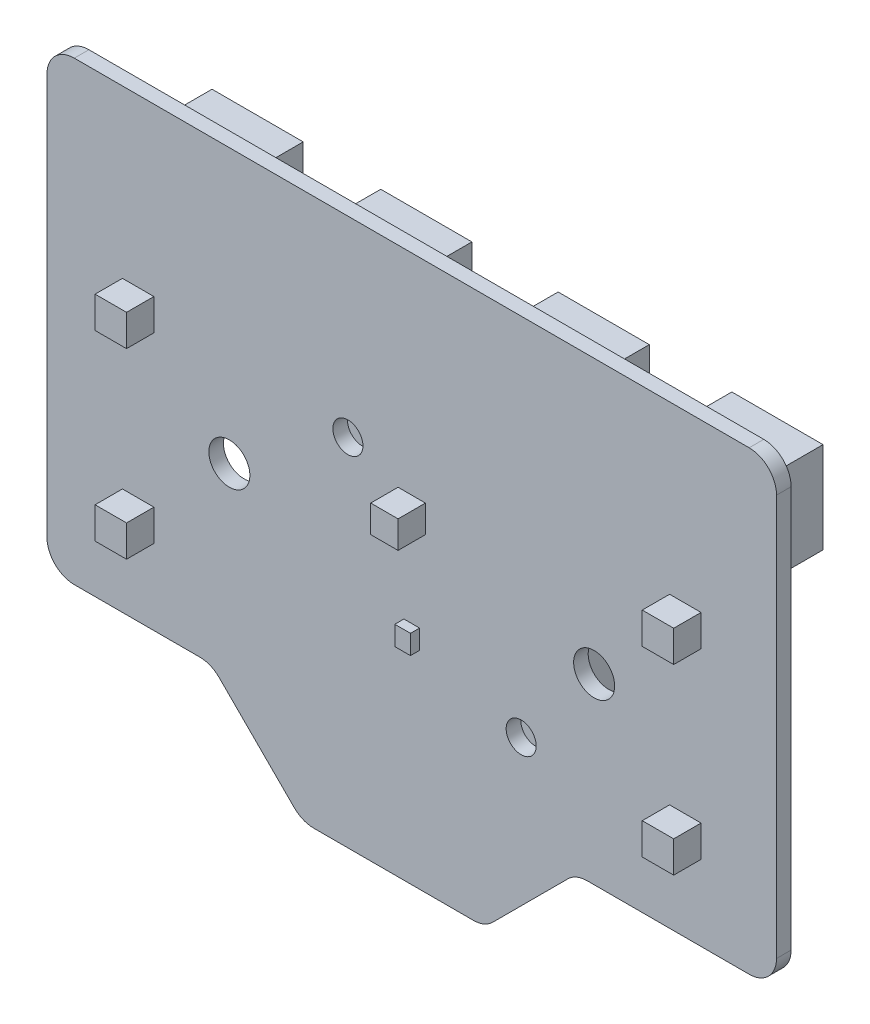
SolidWorks part; units mm, degrees
ref_plane "Plan de face" through (0, 0, 0) normal (0, 0, 1) x (1, 0, 0)
ref_plane "Plan de dessus" through (0, 0, 0) normal (0, 1, 0) x (1, 0, 0)
ref_plane "Plan de droite" through (0, 0, 0) normal (1, 0, 0) x (0, 0, -1)
sketch "Model" plane through (0, 0, 0) normal (0, 0, 1) x (1, 0, 0)
  line L0 (29.2426, -10) -> (46.7574, -10)
  line L1 (48.8787, -9.1213) -> (57.1213, -0.8787)
  line L2 (59.2426, 0) -> (77, 0)
  line L3 (27.1213, -9.1213) -> (18.8787, -0.8787)
  line L4 (16.7574, 0) -> (3, 0)
  line L5 (80, 3) -> (80, 47)
  line L6 (77, 50) -> (3, 50)
  line L7 (0, 3) -> (0, 47)
  line L8 (55, 7) -> (55, 32)
  line L9 (55, 32) -> (30, 32)
  line L10 (30, 32) -> (30, 7)
  line L11 (30, 7) -> (55, 7)
  line L12 (11.725, 31.725) -> (11.725, 28.275)
  line L13 (11.725, 28.275) -> (8.275, 28.275)
  line L14 (8.275, 28.275) -> (8.275, 31.725)
  line L15 (8.275, 31.725) -> (11.725, 31.725)
  line L16 (11.725, 11.725) -> (11.725, 8.275)
  line L17 (11.725, 8.275) -> (8.275, 8.275)
  line L18 (8.275, 8.275) -> (8.275, 11.725)
  line L19 (8.275, 11.725) -> (11.725, 11.725)
  line L20 (47.4, 42.75) -> (47.4, 45.95)
  line L21 (47.4, 45.95) -> (47.4, 47.25)
  line L22 (47.4, 47.25) -> (43.6, 47.25)
  line L23 (43.6, 47.25) -> (43.6, 45.95)
  line L24 (43.6, 45.95) -> (43.6, 42.75)
  line L25 (43.6, 42.75) -> (47.4, 42.75)
  line L26 (47.4, 45.95) -> (43.6, 45.95)
  line L27 (9.65, 43) -> (9.65, 46.2)
  line L28 (9.65, 46.2) -> (9.65, 47.5)
  line L29 (9.65, 47.5) -> (5.85, 47.5)
  line L30 (5.85, 47.5) -> (5.85, 46.2)
  line L31 (5.85, 46.2) -> (5.85, 43)
  line L32 (5.85, 43) -> (9.65, 43)
  line L33 (9.65, 46.2) -> (5.85, 46.2)
  line L34 (66.4, 42.75) -> (66.4, 45.95)
  line L35 (66.4, 45.95) -> (66.4, 47.25)
  line L36 (66.4, 47.25) -> (62.6, 47.25)
  line L37 (62.6, 47.25) -> (62.6, 45.95)
  line L38 (62.6, 45.95) -> (62.6, 42.75)
  line L39 (62.6, 42.75) -> (66.4, 42.75)
  line L40 (66.4, 45.95) -> (62.6, 45.95)
  line L41 (28.07, 42.75) -> (28.07, 45.95)
  line L42 (28.07, 45.95) -> (28.07, 47.25)
  line L43 (28.07, 47.25) -> (24.27, 47.25)
  line L44 (24.27, 47.25) -> (24.27, 45.95)
  line L45 (24.27, 45.95) -> (24.27, 42.75)
  line L46 (24.27, 42.75) -> (28.07, 42.75)
  line L47 (28.07, 45.95) -> (24.27, 45.95)
  line L48 (26.675, -5.9) -> (31, -5.9)
  line L49 (31, -5.9) -> (32, -5.9)
  line L50 (32, -5.9) -> (36.325, -5.9)
  line L51 (36.325, -5.9) -> (36.325, -1.53)
  line L52 (36.325, -1.53) -> (33.25, -1.53)
  line L53 (33.25, -1.53) -> (32.25, -1.53)
  line L54 (32.25, -1.53) -> (30.75, -1.53)
  line L55 (30.75, -1.53) -> (29.75, -1.53)
  line L56 (29.75, -1.53) -> (26.675, -1.53)
  line L57 (26.675, -1.53) -> (26.675, -5.9)
  line L58 (31, -5.9) -> (31, -6.5)
  line L59 (31, -6.5) -> (32, -6.5)
  line L60 (32, -6.5) -> (32, -5.9)
  line L61 (30.75, -1.53) -> (30.75, -0.93)
  line L62 (30.75, -0.93) -> (29.75, -0.93)
  line L63 (29.75, -0.93) -> (29.75, -1.53)
  line L64 (32.25, -1.53) -> (32.25, -0.93)
  line L65 (32.25, -0.93) -> (33.25, -0.93)
  line L66 (33.25, -0.93) -> (33.25, -1.53)
  line L67 (31.75, -5.25) -> (34.25, -5.25)
  line L68 (34.25, -5.25) -> (34.25, -3.25)
  line L69 (34.25, -3.25) -> (33.75, -2.75)
  line L70 (33.75, -2.75) -> (31.75, -2.75)
  line L71 (31.75, -2.75) -> (31.75, -5.25)
  line L72 (28.75, -5.25) -> (31.25, -5.25)
  line L73 (31.25, -5.25) -> (31.25, -2.75)
  line L74 (31.25, -2.75) -> (29.25, -2.75)
  line L75 (29.25, -2.75) -> (28.75, -3.25)
  line L76 (28.75, -3.25) -> (28.75, -5.25)
  line L77 (39.925, -5.9) -> (44.25, -5.9)
  line L78 (44.25, -5.9) -> (45.25, -5.9)
  line L79 (45.25, -5.9) -> (49.575, -5.9)
  line L80 (49.575, -5.9) -> (49.575, -1.53)
  line L81 (49.575, -1.53) -> (46.5, -1.53)
  line L82 (46.5, -1.53) -> (45.5, -1.53)
  line L83 (45.5, -1.53) -> (44, -1.53)
  line L84 (44, -1.53) -> (43, -1.53)
  line L85 (43, -1.53) -> (39.925, -1.53)
  line L86 (39.925, -1.53) -> (39.925, -5.9)
  line L87 (44.25, -5.9) -> (44.25, -6.5)
  line L88 (44.25, -6.5) -> (45.25, -6.5)
  line L89 (45.25, -6.5) -> (45.25, -5.9)
  line L90 (44, -1.53) -> (44, -0.93)
  line L91 (44, -0.93) -> (43, -0.93)
  line L92 (43, -0.93) -> (43, -1.53)
  line L93 (45.5, -1.53) -> (45.5, -0.93)
  line L94 (45.5, -0.93) -> (46.5, -0.93)
  line L95 (46.5, -0.93) -> (46.5, -1.53)
  line L96 (45, -5.25) -> (47.5, -5.25)
  line L97 (47.5, -5.25) -> (47.5, -3.25)
  line L98 (47.5, -3.25) -> (47, -2.75)
  line L99 (47, -2.75) -> (45, -2.75)
  line L100 (45, -2.75) -> (45, -5.25)
  line L101 (42, -5.25) -> (44.5, -5.25)
  line L102 (44.5, -5.25) -> (44.5, -2.75)
  line L103 (44.5, -2.75) -> (42.5, -2.75)
  line L104 (42.5, -2.75) -> (42, -3.25)
  line L105 (42, -3.25) -> (42, -5.25)
  line L106 (21.5, 38) -> (21.5, 48)
  line L107 (21.5, 48) -> (11.5, 48)
  line L108 (11.5, 48) -> (11.5, 38)
  line L109 (11.5, 38) -> (21.5, 38)
  line L110 (16.2908, 37.35) -> (16.2908, 36.4508)
  line L111 (16.2908, 36.4508) -> (15.6913, 36.4508)
  line L112 (15.37, 37.0502) -> (15.0703, 37.35)
  line L113 (15.0703, 37.35) -> (15.0703, 36.4508)
  line L114 (15.37, 36.4508) -> (14.7705, 36.4508)
  line L115 (78.5, 37.75) -> (78.5, 47.75)
  line L116 (78.5, 47.75) -> (68.5, 47.75)
  line L117 (68.5, 47.75) -> (68.5, 37.75)
  line L118 (68.5, 37.75) -> (78.5, 37.75)
  line L119 (73.2908, 37.1) -> (73.2908, 36.2008)
  line L120 (73.2908, 36.2008) -> (72.6913, 36.2008)
  line L121 (71.7705, 36.2008) -> (72.37, 36.2008)
  line L122 (72.37, 36.2008) -> (71.7705, 36.8002)
  line L123 (71.7705, 36.8002) -> (71.7705, 36.9501)
  line L124 (71.7705, 36.9501) -> (71.9204, 37.1)
  line L125 (71.9204, 37.1) -> (72.2201, 37.1)
  line L126 (72.2201, 37.1) -> (72.37, 36.9501)
  line L127 (40, 37.75) -> (40, 47.75)
  line L128 (40, 47.75) -> (30, 47.75)
  line L129 (30, 47.75) -> (30, 37.75)
  line L130 (30, 37.75) -> (40, 37.75)
  line L131 (34.7908, 37.1) -> (34.7908, 36.2008)
  line L132 (34.7908, 36.2008) -> (34.1913, 36.2008)
  line L133 (33.87, 36.9501) -> (33.7201, 37.1)
  line L134 (33.7201, 37.1) -> (33.4204, 37.1)
  line L135 (33.4204, 37.1) -> (33.2705, 36.9501)
  line L136 (33.2705, 36.9501) -> (33.2705, 36.8002)
  line L137 (33.2705, 36.8002) -> (33.4204, 36.6504)
  line L138 (33.4204, 36.6504) -> (33.5703, 36.6504)
  line L139 (33.4204, 36.6504) -> (33.2705, 36.5005)
  line L140 (33.2705, 36.5005) -> (33.2705, 36.3507)
  line L141 (33.2705, 36.3507) -> (33.4204, 36.2008)
  line L142 (33.4204, 36.2008) -> (33.7201, 36.2008)
  line L143 (33.7201, 36.2008) -> (33.87, 36.3507)
  line L144 (59.45, 37.72) -> (59.45, 47.72)
  line L145 (59.45, 47.72) -> (49.45, 47.72)
  line L146 (49.45, 47.72) -> (49.45, 37.72)
  line L147 (49.45, 37.72) -> (59.45, 37.72)
  line L148 (54.2408, 37.07) -> (54.2408, 36.1708)
  line L149 (54.2408, 36.1708) -> (53.6413, 36.1708)
  line L150 (52.7205, 37.07) -> (53.32, 37.07)
  line L151 (53.32, 37.07) -> (53.32, 36.6204)
  line L152 (53.32, 36.6204) -> (53.0203, 36.7702)
  line L153 (53.0203, 36.7702) -> (52.8704, 36.7702)
  line L154 (52.8704, 36.7702) -> (52.7205, 36.6204)
  line L155 (52.7205, 36.6204) -> (52.7205, 36.3207)
  line L156 (52.7205, 36.3207) -> (52.8704, 36.1708)
  line L157 (52.8704, 36.1708) -> (53.1701, 36.1708)
  line L158 (53.1701, 36.1708) -> (53.32, 36.3207)
  line L159 (68.275, 31.725) -> (71.725, 31.725)
  line L160 (71.725, 31.725) -> (71.725, 28.275)
  line L161 (71.725, 28.275) -> (68.275, 28.275)
  line L162 (68.275, 28.275) -> (68.275, 31.725)
  line L163 (68.275, 11.725) -> (71.725, 11.725)
  line L164 (71.725, 11.725) -> (71.725, 8.275)
  line L165 (71.725, 8.275) -> (68.275, 8.275)
  line L166 (68.275, 8.275) -> (68.275, 11.725)
  line L167 (10.422, 37.44) -> (10.422, 39.06)
  line L168 (7.578, 39.06) -> (7.578, 37.44)
  line L169 (8.478, 37.44) -> (9.522, 37.44)
  line L170 (8.572, 39.06) -> (8.478, 39.06)
  line L171 (9.522, 39.06) -> (9.428, 39.06)
  line L172 (7.672, 39.06) -> (7.578, 39.06)
  line L173 (10.422, 39.06) -> (10.328, 39.06)
  line L174 (10.328, 37.44) -> (10.422, 37.44)
  line L175 (7.578, 37.44) -> (7.672, 37.44)
  line L176 (66.922, 36.69) -> (66.922, 38.31)
  line L177 (64.078, 38.31) -> (64.078, 36.69)
  line L178 (64.978, 36.69) -> (66.022, 36.69)
  line L179 (65.072, 38.31) -> (64.978, 38.31)
  line L180 (66.022, 38.31) -> (65.928, 38.31)
  line L181 (64.172, 38.31) -> (64.078, 38.31)
  line L182 (66.922, 38.31) -> (66.828, 38.31)
  line L183 (66.828, 36.69) -> (66.922, 36.69)
  line L184 (64.078, 36.69) -> (64.172, 36.69)
  line L185 (28.922, 36.94) -> (28.922, 38.56)
  line L186 (26.078, 38.56) -> (26.078, 36.94)
  line L187 (26.978, 36.94) -> (28.022, 36.94)
  line L188 (27.072, 38.56) -> (26.978, 38.56)
  line L189 (28.022, 38.56) -> (27.928, 38.56)
  line L190 (26.172, 38.56) -> (26.078, 38.56)
  line L191 (28.922, 38.56) -> (28.828, 38.56)
  line L192 (28.828, 36.94) -> (28.922, 36.94)
  line L193 (26.078, 36.94) -> (26.172, 36.94)
  line L194 (47.922, 37.19) -> (47.922, 38.81)
  line L195 (45.078, 38.81) -> (45.078, 37.19)
  line L196 (45.978, 37.19) -> (47.022, 37.19)
  line L197 (46.072, 38.81) -> (45.978, 38.81)
  line L198 (47.022, 38.81) -> (46.928, 38.81)
  line L199 (45.172, 38.81) -> (45.078, 38.81)
  line L200 (47.922, 38.81) -> (47.828, 38.81)
  line L201 (47.828, 37.19) -> (47.922, 37.19)
  line L202 (45.078, 37.19) -> (45.172, 37.19)
  line L203 (40.86, 14.81) -> (40.86, 13.86)
  line L204 (40.86, 13.86) -> (40.75, 13.75)
  line L205 (40.75, 13.75) -> (40.86, 13.64)
  line L206 (40.86, 13.64) -> (40.86, 12.69)
  line L207 (40.86, 12.69) -> (39.14, 12.69)
  line L208 (39.14, 12.69) -> (39.14, 14.81)
  line L209 (39.14, 14.81) -> (40.86, 14.81)
  line L210 (41.5, 24) -> (38.5, 24)
  line L211 (38.5, 24) -> (38.5, 27)
  line L212 (38.5, 27) -> (41.5, 27)
  line L213 (41.5, 27) -> (41.5, 24)
  arc A0 (46.7574, -10) -> (48.8787, -9.1213) centre (46.7574, -7) ccw
  arc A1 (59.2426, 0) -> (57.1213, -0.8787) centre (59.2426, -3) ccw
  arc A2 (27.1213, -9.1213) -> (29.2426, -10) centre (29.2426, -7) ccw
  arc A3 (18.8787, -0.8787) -> (16.7574, 0) centre (16.7574, -3) ccw
  arc A4 (77, 0) -> (80, 3) centre (77, 3) ccw
  arc A5 (80, 47) -> (77, 50) centre (77, 47) ccw
  arc A6 (3, 50) -> (0, 47) centre (3, 47) ccw
  arc A7 (0, 3) -> (3, 0) centre (3, 3) ccw
  circle A8 centre (20, 20) radius 2.25
  circle A9 centre (60, 20) radius 2.25
  circle A10 centre (33, 29) radius 1.65
  circle A11 centre (52, 10) radius 1.65
  circle A12 centre (27, -5.96) radius 0.55
  circle A13 centre (36, -5.96) radius 0.55
  circle A14 centre (40.25, -5.96) radius 0.55
  circle A15 centre (49.25, -5.96) radius 0.55
  arc A16 (55.05, 32) -> (54.95, 32) centre (55, 32) ccw
  arc A17 (54.95, 7) -> (55.05, 7) centre (55, 7) ccw
  arc A18 (30, 32.05) -> (30, 31.95) centre (30, 32) ccw
  arc A19 (55, 31.95) -> (55, 32.05) centre (55, 32) ccw
  arc A20 (29.95, 7) -> (30.05, 7) centre (30, 7) ccw
  arc A21 (30.05, 32) -> (29.95, 32) centre (30, 32) ccw
  arc A22 (55, 6.95) -> (55, 7.05) centre (55, 7) ccw
  arc A23 (30, 7.05) -> (30, 6.95) centre (30, 7) ccw
  arc A24 (11.7125, 28.275) -> (11.7375, 28.275) centre (11.725, 28.275) ccw
  arc A25 (11.7375, 31.725) -> (11.7125, 31.725) centre (11.725, 31.725) ccw
  arc A26 (8.275, 28.2875) -> (8.275, 28.2625) centre (8.275, 28.275) ccw
  arc A27 (11.725, 28.2625) -> (11.725, 28.2875) centre (11.725, 28.275) ccw
  arc A28 (8.2875, 31.725) -> (8.2625, 31.725) centre (8.275, 31.725) ccw
  arc A29 (8.2625, 28.275) -> (8.2875, 28.275) centre (8.275, 28.275) ccw
  arc A30 (11.725, 31.7125) -> (11.725, 31.7375) centre (11.725, 31.725) ccw
  arc A31 (8.275, 31.7375) -> (8.275, 31.7125) centre (8.275, 31.725) ccw
  arc A32 (11.7125, 8.275) -> (11.7375, 8.275) centre (11.725, 8.275) ccw
  arc A33 (11.7375, 11.725) -> (11.7125, 11.725) centre (11.725, 11.725) ccw
  arc A34 (8.275, 8.2875) -> (8.275, 8.2625) centre (8.275, 8.275) ccw
  arc A35 (11.725, 8.2625) -> (11.725, 8.2875) centre (11.725, 8.275) ccw
  arc A36 (8.2875, 11.725) -> (8.2625, 11.725) centre (8.275, 11.725) ccw
  arc A37 (8.2625, 8.275) -> (8.2875, 8.275) centre (8.275, 8.275) ccw
  arc A38 (11.725, 11.7125) -> (11.725, 11.7375) centre (11.725, 11.725) ccw
  arc A39 (8.275, 11.7375) -> (8.275, 11.7125) centre (8.275, 11.725) ccw
  arc A40 (47.4635, 45.95) -> (47.3365, 45.95) centre (47.4, 45.95) ccw
  arc A41 (47.3365, 42.75) -> (47.4635, 42.75) centre (47.4, 42.75) ccw
  arc A42 (47.4635, 47.25) -> (47.3365, 47.25) centre (47.4, 47.25) ccw
  arc A43 (47.3365, 45.95) -> (47.4635, 45.95) centre (47.4, 45.95) ccw
  arc A44 (43.6, 47.3135) -> (43.6, 47.1865) centre (43.6, 47.25) ccw
  arc A45 (47.4, 47.1865) -> (47.4, 47.3135) centre (47.4, 47.25) ccw
  arc A46 (43.5365, 45.95) -> (43.6635, 45.95) centre (43.6, 45.95) ccw
  arc A47 (43.6635, 47.25) -> (43.5365, 47.25) centre (43.6, 47.25) ccw
  arc A48 (43.5365, 42.75) -> (43.6635, 42.75) centre (43.6, 42.75) ccw
  arc A49 (43.6635, 45.95) -> (43.5365, 45.95) centre (43.6, 45.95) ccw
  arc A50 (47.4, 42.6865) -> (47.4, 42.8135) centre (47.4, 42.75) ccw
  arc A51 (43.6, 42.8135) -> (43.6, 42.6865) centre (43.6, 42.75) ccw
  arc A52 (43.6, 46.0135) -> (43.6, 45.8865) centre (43.6, 45.95) ccw
  arc A53 (47.4, 45.8865) -> (47.4, 46.0135) centre (47.4, 45.95) ccw
  arc A54 (9.7135, 46.2) -> (9.5865, 46.2) centre (9.65, 46.2) ccw
  arc A55 (9.5865, 43) -> (9.7135, 43) centre (9.65, 43) ccw
  arc A56 (9.7135, 47.5) -> (9.5865, 47.5) centre (9.65, 47.5) ccw
  arc A57 (9.5865, 46.2) -> (9.7135, 46.2) centre (9.65, 46.2) ccw
  arc A58 (5.85, 47.5635) -> (5.85, 47.4365) centre (5.85, 47.5) ccw
  arc A59 (9.65, 47.4365) -> (9.65, 47.5635) centre (9.65, 47.5) ccw
  arc A60 (5.7865, 46.2) -> (5.9135, 46.2) centre (5.85, 46.2) ccw
  arc A61 (5.9135, 47.5) -> (5.7865, 47.5) centre (5.85, 47.5) ccw
  arc A62 (5.7865, 43) -> (5.9135, 43) centre (5.85, 43) ccw
  arc A63 (5.9135, 46.2) -> (5.7865, 46.2) centre (5.85, 46.2) ccw
  arc A64 (9.65, 42.9365) -> (9.65, 43.0635) centre (9.65, 43) ccw
  arc A65 (5.85, 43.0635) -> (5.85, 42.9365) centre (5.85, 43) ccw
  arc A66 (5.85, 46.2635) -> (5.85, 46.1365) centre (5.85, 46.2) ccw
  arc A67 (9.65, 46.1365) -> (9.65, 46.2635) centre (9.65, 46.2) ccw
  arc A68 (66.4635, 45.95) -> (66.3365, 45.95) centre (66.4, 45.95) ccw
  arc A69 (66.3365, 42.75) -> (66.4635, 42.75) centre (66.4, 42.75) ccw
  arc A70 (66.4635, 47.25) -> (66.3365, 47.25) centre (66.4, 47.25) ccw
  arc A71 (66.3365, 45.95) -> (66.4635, 45.95) centre (66.4, 45.95) ccw
  arc A72 (62.6, 47.3135) -> (62.6, 47.1865) centre (62.6, 47.25) ccw
  arc A73 (66.4, 47.1865) -> (66.4, 47.3135) centre (66.4, 47.25) ccw
  arc A74 (62.5365, 45.95) -> (62.6635, 45.95) centre (62.6, 45.95) ccw
  arc A75 (62.6635, 47.25) -> (62.5365, 47.25) centre (62.6, 47.25) ccw
  arc A76 (62.5365, 42.75) -> (62.6635, 42.75) centre (62.6, 42.75) ccw
  arc A77 (62.6635, 45.95) -> (62.5365, 45.95) centre (62.6, 45.95) ccw
  arc A78 (66.4, 42.6865) -> (66.4, 42.8135) centre (66.4, 42.75) ccw
  arc A79 (62.6, 42.8135) -> (62.6, 42.6865) centre (62.6, 42.75) ccw
  arc A80 (62.6, 46.0135) -> (62.6, 45.8865) centre (62.6, 45.95) ccw
  arc A81 (66.4, 45.8865) -> (66.4, 46.0135) centre (66.4, 45.95) ccw
  arc A82 (28.1335, 45.95) -> (28.0065, 45.95) centre (28.07, 45.95) ccw
  arc A83 (28.0065, 42.75) -> (28.1335, 42.75) centre (28.07, 42.75) ccw
  arc A84 (28.1335, 47.25) -> (28.0065, 47.25) centre (28.07, 47.25) ccw
  arc A85 (28.0065, 45.95) -> (28.1335, 45.95) centre (28.07, 45.95) ccw
  arc A86 (24.27, 47.3135) -> (24.27, 47.1865) centre (24.27, 47.25) ccw
  arc A87 (28.07, 47.1865) -> (28.07, 47.3135) centre (28.07, 47.25) ccw
  arc A88 (24.2065, 45.95) -> (24.3335, 45.95) centre (24.27, 45.95) ccw
  arc A89 (24.3335, 47.25) -> (24.2065, 47.25) centre (24.27, 47.25) ccw
  arc A90 (24.2065, 42.75) -> (24.3335, 42.75) centre (24.27, 42.75) ccw
  arc A91 (24.3335, 45.95) -> (24.2065, 45.95) centre (24.27, 45.95) ccw
  arc A92 (28.07, 42.6865) -> (28.07, 42.8135) centre (28.07, 42.75) ccw
  arc A93 (24.27, 42.8135) -> (24.27, 42.6865) centre (24.27, 42.75) ccw
  arc A94 (24.27, 46.0135) -> (24.27, 45.8865) centre (24.27, 45.95) ccw
  arc A95 (28.07, 45.8865) -> (28.07, 46.0135) centre (28.07, 45.95) ccw
  arc A96 (31, -5.9318) -> (31, -5.8683) centre (31, -5.9001) ccw
  arc A97 (26.675, -5.8683) -> (26.675, -5.9318) centre (26.675, -5.9001) ccw
  arc A98 (32, -5.9318) -> (32, -5.8683) centre (32, -5.9001) ccw
  arc A99 (31, -5.8683) -> (31, -5.9318) centre (31, -5.9001) ccw
  arc A100 (36.325, -5.9318) -> (36.325, -5.8683) centre (36.325, -5.9001) ccw
  arc A101 (32, -5.8683) -> (32, -5.9318) centre (32, -5.9001) ccw
  arc A102 (36.3568, -1.53) -> (36.2933, -1.53) centre (36.325, -1.53) ccw
  arc A103 (36.2933, -5.9) -> (36.3568, -5.9) centre (36.325, -5.9) ccw
  arc A104 (33.25, -1.4983) -> (33.25, -1.5617) centre (33.25, -1.53) ccw
  arc A105 (36.325, -1.5617) -> (36.325, -1.4983) centre (36.325, -1.53) ccw
  arc A106 (32.25, -1.4983) -> (32.25, -1.5617) centre (32.25, -1.53) ccw
  arc A107 (33.25, -1.5617) -> (33.25, -1.4983) centre (33.25, -1.53) ccw
  arc A108 (30.75, -1.4983) -> (30.75, -1.5617) centre (30.75, -1.53) ccw
  arc A109 (32.25, -1.5617) -> (32.25, -1.4983) centre (32.25, -1.53) ccw
  arc A110 (29.75, -1.4983) -> (29.75, -1.5617) centre (29.75, -1.53) ccw
  arc A111 (30.75, -1.5617) -> (30.75, -1.4983) centre (30.75, -1.53) ccw
  arc A112 (26.675, -1.4983) -> (26.675, -1.5617) centre (26.675, -1.53) ccw
  arc A113 (29.75, -1.5617) -> (29.75, -1.4983) centre (29.75, -1.53) ccw
  arc A114 (26.6433, -5.9) -> (26.7067, -5.9) centre (26.675, -5.9) ccw
  arc A115 (26.7067, -1.53) -> (26.6433, -1.53) centre (26.675, -1.53) ccw
  arc A116 (30.9683, -6.5) -> (31.0317, -6.5) centre (31, -6.5) ccw
  arc A117 (31.0317, -5.9) -> (30.9683, -5.9) centre (31, -5.9) ccw
  arc A118 (32, -6.5317) -> (32, -6.4683) centre (32, -6.5) ccw
  arc A119 (31, -6.4683) -> (31, -6.5317) centre (31, -6.5) ccw
  arc A120 (32.0318, -5.9) -> (31.9683, -5.9) centre (32.0001, -5.9) ccw
  arc A121 (31.9683, -6.5) -> (32.0318, -6.5) centre (32.0001, -6.5) ccw
  arc A122 (30.7817, -0.93) -> (30.7183, -0.93) centre (30.75, -0.93) ccw
  arc A123 (30.7183, -1.53) -> (30.7817, -1.53) centre (30.75, -1.53) ccw
  arc A124 (29.75, -0.8982) -> (29.75, -0.9618) centre (29.75, -0.93) ccw
  arc A125 (30.75, -0.9618) -> (30.75, -0.8982) centre (30.75, -0.93) ccw
  arc A126 (29.7183, -1.53) -> (29.7817, -1.53) centre (29.75, -1.53) ccw
  arc A127 (29.7817, -0.93) -> (29.7183, -0.93) centre (29.75, -0.93) ccw
  arc A128 (32.2818, -0.93) -> (32.2182, -0.93) centre (32.25, -0.93) ccw
  arc A129 (32.2182, -1.53) -> (32.2818, -1.53) centre (32.25, -1.53) ccw
  arc A130 (33.25, -0.9618) -> (33.25, -0.8982) centre (33.25, -0.93) ccw
  arc A131 (32.25, -0.8982) -> (32.25, -0.9618) centre (32.25, -0.93) ccw
  arc A132 (33.2182, -1.53) -> (33.2818, -1.53) centre (33.25, -1.53) ccw
  arc A133 (33.2818, -0.93) -> (33.2182, -0.93) centre (33.25, -0.93) ccw
  arc A134 (34.25, -5.2817) -> (34.25, -5.2183) centre (34.25, -5.25) ccw
  arc A135 (31.75, -5.2183) -> (31.75, -5.2817) centre (31.75, -5.25) ccw
  arc A136 (34.2818, -3.25) -> (34.2182, -3.25) centre (34.25, -3.25) ccw
  arc A137 (34.2182, -5.25) -> (34.2818, -5.25) centre (34.25, -5.25) ccw
  arc A138 (33.7725, -2.7275) -> (33.7275, -2.7725) centre (33.75, -2.75) ccw
  arc A139 (34.2275, -3.2725) -> (34.2725, -3.2275) centre (34.25, -3.25) ccw
  arc A140 (31.75, -2.7182) -> (31.75, -2.7818) centre (31.75, -2.75) ccw
  arc A141 (33.75, -2.7818) -> (33.75, -2.7182) centre (33.75, -2.75) ccw
  arc A142 (31.7183, -5.25) -> (31.7817, -5.25) centre (31.75, -5.25) ccw
  arc A143 (31.7817, -2.75) -> (31.7183, -2.75) centre (31.75, -2.75) ccw
  arc A144 (31.25, -5.2817) -> (31.25, -5.2183) centre (31.25, -5.25) ccw
  arc A145 (28.75, -5.2183) -> (28.75, -5.2817) centre (28.75, -5.25) ccw
  arc A146 (31.2817, -2.75) -> (31.2183, -2.75) centre (31.25, -2.75) ccw
  arc A147 (31.2183, -5.25) -> (31.2817, -5.25) centre (31.25, -5.25) ccw
  arc A148 (29.25, -2.7182) -> (29.25, -2.7818) centre (29.25, -2.75) ccw
  arc A149 (31.25, -2.7818) -> (31.25, -2.7182) centre (31.25, -2.75) ccw
  arc A150 (28.7275, -3.2275) -> (28.7725, -3.2725) centre (28.75, -3.25) ccw
  arc A151 (29.2725, -2.7725) -> (29.2275, -2.7275) centre (29.25, -2.75) ccw
  arc A152 (28.7183, -5.25) -> (28.7817, -5.25) centre (28.75, -5.25) ccw
  arc A153 (28.7817, -3.25) -> (28.7183, -3.25) centre (28.75, -3.25) ccw
  arc A154 (44.25, -5.9318) -> (44.25, -5.8683) centre (44.25, -5.9001) ccw
  arc A155 (39.925, -5.8683) -> (39.925, -5.9318) centre (39.925, -5.9001) ccw
  arc A156 (45.25, -5.9318) -> (45.25, -5.8683) centre (45.25, -5.9001) ccw
  arc A157 (44.25, -5.8683) -> (44.25, -5.9318) centre (44.25, -5.9001) ccw
  arc A158 (49.575, -5.9318) -> (49.575, -5.8683) centre (49.575, -5.9001) ccw
  arc A159 (45.25, -5.8683) -> (45.25, -5.9318) centre (45.25, -5.9001) ccw
  arc A160 (49.6068, -1.53) -> (49.5433, -1.53) centre (49.5751, -1.53) ccw
  arc A161 (49.5433, -5.9) -> (49.6068, -5.9) centre (49.5751, -5.9) ccw
  arc A162 (46.5, -1.4983) -> (46.5, -1.5617) centre (46.5, -1.53) ccw
  arc A163 (49.575, -1.5617) -> (49.575, -1.4983) centre (49.575, -1.53) ccw
  arc A164 (45.5, -1.4983) -> (45.5, -1.5617) centre (45.5, -1.53) ccw
  arc A165 (46.5, -1.5617) -> (46.5, -1.4983) centre (46.5, -1.53) ccw
  arc A166 (44, -1.4983) -> (44, -1.5617) centre (44, -1.53) ccw
  arc A167 (45.5, -1.5617) -> (45.5, -1.4983) centre (45.5, -1.53) ccw
  arc A168 (43, -1.4983) -> (43, -1.5617) centre (43, -1.53) ccw
  arc A169 (44, -1.5617) -> (44, -1.4983) centre (44, -1.53) ccw
  arc A170 (39.925, -1.4983) -> (39.925, -1.5617) centre (39.925, -1.53) ccw
  arc A171 (43, -1.5617) -> (43, -1.4983) centre (43, -1.53) ccw
  arc A172 (39.8933, -5.9) -> (39.9568, -5.9) centre (39.9251, -5.9) ccw
  arc A173 (39.9568, -1.53) -> (39.8933, -1.53) centre (39.9251, -1.53) ccw
  arc A174 (44.2182, -6.5) -> (44.2818, -6.5) centre (44.25, -6.5) ccw
  arc A175 (44.2818, -5.9) -> (44.2182, -5.9) centre (44.25, -5.9) ccw
  arc A176 (45.25, -6.5317) -> (45.25, -6.4683) centre (45.25, -6.5) ccw
  arc A177 (44.25, -6.4683) -> (44.25, -6.5317) centre (44.25, -6.5) ccw
  arc A178 (45.2818, -5.9) -> (45.2182, -5.9) centre (45.25, -5.9) ccw
  arc A179 (45.2182, -6.5) -> (45.2818, -6.5) centre (45.25, -6.5) ccw
  arc A180 (44.0318, -0.93) -> (43.9682, -0.93) centre (44, -0.93) ccw
  arc A181 (43.9682, -1.53) -> (44.0318, -1.53) centre (44, -1.53) ccw
  arc A182 (43, -0.8982) -> (43, -0.9618) centre (43, -0.93) ccw
  arc A183 (44, -0.9618) -> (44, -0.8982) centre (44, -0.93) ccw
  arc A184 (42.9682, -1.53) -> (43.0318, -1.53) centre (43, -1.53) ccw
  arc A185 (43.0318, -0.93) -> (42.9682, -0.93) centre (43, -0.93) ccw
  arc A186 (45.5318, -0.93) -> (45.4682, -0.93) centre (45.5, -0.93) ccw
  arc A187 (45.4682, -1.53) -> (45.5318, -1.53) centre (45.5, -1.53) ccw
  arc A188 (46.5, -0.9618) -> (46.5, -0.8982) centre (46.5, -0.93) ccw
  arc A189 (45.5, -0.8982) -> (45.5, -0.9618) centre (45.5, -0.93) ccw
  arc A190 (46.4682, -1.53) -> (46.5318, -1.53) centre (46.5, -1.53) ccw
  arc A191 (46.5318, -0.93) -> (46.4682, -0.93) centre (46.5, -0.93) ccw
  arc A192 (47.5, -5.2817) -> (47.5, -5.2183) centre (47.5, -5.25) ccw
  arc A193 (45, -5.2183) -> (45, -5.2817) centre (45, -5.25) ccw
  arc A194 (47.5318, -3.25) -> (47.4682, -3.25) centre (47.5, -3.25) ccw
  arc A195 (47.4682, -5.25) -> (47.5318, -5.25) centre (47.5, -5.25) ccw
  arc A196 (47.0225, -2.7275) -> (46.9775, -2.7725) centre (47, -2.75) ccw
  arc A197 (47.4775, -3.2725) -> (47.5225, -3.2275) centre (47.5, -3.25) ccw
  arc A198 (45, -2.7182) -> (45, -2.7818) centre (45, -2.75) ccw
  arc A199 (47, -2.7818) -> (47, -2.7182) centre (47, -2.75) ccw
  arc A200 (44.9682, -5.25) -> (45.0318, -5.25) centre (45, -5.25) ccw
  arc A201 (45.0318, -2.75) -> (44.9682, -2.75) centre (45, -2.75) ccw
  arc A202 (44.5, -5.2817) -> (44.5, -5.2183) centre (44.5, -5.25) ccw
  arc A203 (42, -5.2183) -> (42, -5.2817) centre (42, -5.25) ccw
  arc A204 (44.5318, -2.75) -> (44.4682, -2.75) centre (44.5, -2.75) ccw
  arc A205 (44.4682, -5.25) -> (44.5318, -5.25) centre (44.5, -5.25) ccw
  arc A206 (42.5, -2.7182) -> (42.5, -2.7818) centre (42.5, -2.75) ccw
  arc A207 (44.5, -2.7818) -> (44.5, -2.7182) centre (44.5, -2.75) ccw
  arc A208 (41.9775, -3.2275) -> (42.0225, -3.2725) centre (42, -3.25) ccw
  arc A209 (42.5225, -2.7725) -> (42.4775, -2.7275) centre (42.5, -2.75) ccw
  arc A210 (41.9682, -5.25) -> (42.0318, -5.25) centre (42, -5.25) ccw
  arc A211 (42.0318, -3.25) -> (41.9682, -3.25) centre (42, -3.25) ccw
  arc A212 (21.525, 48) -> (21.475, 48) centre (21.5, 48) ccw
  arc A213 (21.475, 38) -> (21.525, 38) centre (21.5, 38) ccw
  arc A214 (11.5, 48.025) -> (11.5, 47.975) centre (11.5, 48) ccw
  arc A215 (21.5, 47.975) -> (21.5, 48.025) centre (21.5, 48) ccw
  arc A216 (11.475, 38) -> (11.525, 38) centre (11.5, 38) ccw
  arc A217 (11.525, 48) -> (11.475, 48) centre (11.5, 48) ccw
  arc A218 (21.5, 37.975) -> (21.5, 38.025) centre (21.5, 38) ccw
  arc A219 (11.5, 38.025) -> (11.5, 37.975) centre (11.5, 38) ccw
  arc A220 (16.2654, 36.4508) -> (16.3162, 36.4508) centre (16.2908, 36.4508) ccw
  arc A221 (16.3162, 37.35) -> (16.2654, 37.35) centre (16.2908, 37.35) ccw
  arc A222 (15.6913, 36.4762) -> (15.6913, 36.4254) centre (15.6913, 36.4508) ccw
  arc A223 (16.2908, 36.4254) -> (16.2908, 36.4762) centre (16.2908, 36.4508) ccw
  arc A224 (15.0882, 37.3679) -> (15.0523, 37.332) centre (15.0702, 37.35) ccw
  arc A225 (15.352, 37.0323) -> (15.3879, 37.0682) centre (15.37, 37.0502) ccw
  arc A226 (15.0449, 36.4508) -> (15.0957, 36.4508) centre (15.0703, 36.4508) ccw
  arc A227 (15.0957, 37.35) -> (15.0449, 37.35) centre (15.0703, 37.35) ccw
  arc A228 (14.7705, 36.4762) -> (14.7705, 36.4254) centre (14.7705, 36.4508) ccw
  arc A229 (15.37, 36.4254) -> (15.37, 36.4762) centre (15.37, 36.4508) ccw
  arc A230 (78.525, 47.75) -> (78.475, 47.75) centre (78.5, 47.75) ccw
  arc A231 (78.475, 37.75) -> (78.525, 37.75) centre (78.5, 37.75) ccw
  arc A232 (68.5, 47.775) -> (68.5, 47.725) centre (68.5, 47.75) ccw
  arc A233 (78.5, 47.725) -> (78.5, 47.775) centre (78.5, 47.75) ccw
  arc A234 (68.475, 37.75) -> (68.525, 37.75) centre (68.5, 37.75) ccw
  arc A235 (68.525, 47.75) -> (68.475, 47.75) centre (68.5, 47.75) ccw
  arc A236 (78.5, 37.725) -> (78.5, 37.775) centre (78.5, 37.75) ccw
  arc A237 (68.5, 37.775) -> (68.5, 37.725) centre (68.5, 37.75) ccw
  arc A238 (73.2654, 36.2008) -> (73.3162, 36.2008) centre (73.2908, 36.2008) ccw
  arc A239 (73.3162, 37.1) -> (73.2654, 37.1) centre (73.2908, 37.1) ccw
  arc A240 (72.6913, 36.2262) -> (72.6913, 36.1754) centre (72.6913, 36.2008) ccw
  arc A241 (73.2908, 36.1754) -> (73.2908, 36.2262) centre (73.2908, 36.2008) ccw
  arc A242 (72.37, 36.1754) -> (72.37, 36.2262) centre (72.37, 36.2008) ccw
  arc A243 (71.7705, 36.2262) -> (71.7705, 36.1754) centre (71.7705, 36.2008) ccw
  arc A244 (71.7885, 36.8182) -> (71.7526, 36.7823) centre (71.7706, 36.8002) ccw
  arc A245 (72.352, 36.1828) -> (72.3879, 36.2188) centre (72.37, 36.2008) ccw
  arc A246 (71.7959, 36.9501) -> (71.7451, 36.9501) centre (71.7705, 36.9501) ccw
  arc A247 (71.7451, 36.8002) -> (71.7959, 36.8002) centre (71.7705, 36.8002) ccw
  arc A248 (71.9384, 37.082) -> (71.9024, 37.1179) centre (71.9204, 37.1) ccw
  arc A249 (71.7526, 36.9681) -> (71.7885, 36.9321) centre (71.7706, 36.9501) ccw
  arc A250 (72.2201, 37.0746) -> (72.2201, 37.1254) centre (72.2201, 37.1) ccw
  arc A251 (71.9204, 37.1254) -> (71.9204, 37.0746) centre (71.9204, 37.1) ccw
  arc A252 (72.352, 36.9321) -> (72.3879, 36.9681) centre (72.37, 36.9501) ccw
  arc A253 (72.2381, 37.1179) -> (72.2022, 37.082) centre (72.2202, 37.1) ccw
  arc A254 (40.025, 47.75) -> (39.975, 47.75) centre (40, 47.75) ccw
  arc A255 (39.975, 37.75) -> (40.025, 37.75) centre (40, 37.75) ccw
  arc A256 (30, 47.775) -> (30, 47.725) centre (30, 47.75) ccw
  arc A257 (40, 47.725) -> (40, 47.775) centre (40, 47.75) ccw
  arc A258 (29.975, 37.75) -> (30.025, 37.75) centre (30, 37.75) ccw
  arc A259 (30.025, 47.75) -> (29.975, 47.75) centre (30, 47.75) ccw
  arc A260 (40, 37.725) -> (40, 37.775) centre (40, 37.75) ccw
  arc A261 (30, 37.775) -> (30, 37.725) centre (30, 37.75) ccw
  arc A262 (34.7654, 36.2008) -> (34.8162, 36.2008) centre (34.7908, 36.2008) ccw
  arc A263 (34.8162, 37.1) -> (34.7654, 37.1) centre (34.7908, 37.1) ccw
  arc A264 (34.1913, 36.2262) -> (34.1913, 36.1754) centre (34.1913, 36.2008) ccw
  arc A265 (34.7908, 36.1754) -> (34.7908, 36.2262) centre (34.7908, 36.2008) ccw
  arc A266 (33.7381, 37.1179) -> (33.7022, 37.082) centre (33.7202, 37.1) ccw
  arc A267 (33.852, 36.9321) -> (33.8879, 36.9681) centre (33.87, 36.9501) ccw
  arc A268 (33.4204, 37.1254) -> (33.4204, 37.0746) centre (33.4204, 37.1) ccw
  arc A269 (33.7201, 37.0746) -> (33.7201, 37.1254) centre (33.7201, 37.1) ccw
  arc A270 (33.2526, 36.9681) -> (33.2885, 36.9321) centre (33.2705, 36.9501) ccw
  arc A271 (33.4384, 37.082) -> (33.4024, 37.1179) centre (33.4204, 37.1) ccw
  arc A272 (33.2451, 36.8002) -> (33.2959, 36.8002) centre (33.2705, 36.8002) ccw
  arc A273 (33.2959, 36.9501) -> (33.2451, 36.9501) centre (33.2705, 36.9501) ccw
  arc A274 (33.4024, 36.6324) -> (33.4384, 36.6683) centre (33.4204, 36.6503) ccw
  arc A275 (33.2885, 36.8182) -> (33.2526, 36.7823) centre (33.2705, 36.8002) ccw
  arc A276 (33.5703, 36.625) -> (33.5703, 36.6758) centre (33.5703, 36.6504) ccw
  arc A277 (33.4204, 36.6758) -> (33.4204, 36.625) centre (33.4204, 36.6504) ccw
  arc A278 (33.2526, 36.5185) -> (33.2885, 36.4826) centre (33.2705, 36.5005) ccw
  arc A279 (33.4384, 36.6324) -> (33.4024, 36.6683) centre (33.4204, 36.6503) ccw
  arc A280 (33.2451, 36.3507) -> (33.2959, 36.3507) centre (33.2705, 36.3507) ccw
  arc A281 (33.2959, 36.5005) -> (33.2451, 36.5005) centre (33.2705, 36.5005) ccw
  arc A282 (33.4024, 36.1828) -> (33.4384, 36.2188) centre (33.4204, 36.2008) ccw
  arc A283 (33.2885, 36.3686) -> (33.2526, 36.3327) centre (33.2705, 36.3507) ccw
  arc A284 (33.7201, 36.1754) -> (33.7201, 36.2262) centre (33.7201, 36.2008) ccw
  arc A285 (33.4204, 36.2262) -> (33.4204, 36.1754) centre (33.4204, 36.2008) ccw
  arc A286 (33.8879, 36.3327) -> (33.852, 36.3686) centre (33.87, 36.3507) ccw
  arc A287 (33.7022, 36.2188) -> (33.7381, 36.1828) centre (33.7202, 36.2008) ccw
  arc A288 (59.475, 47.72) -> (59.425, 47.72) centre (59.45, 47.72) ccw
  arc A289 (59.425, 37.72) -> (59.475, 37.72) centre (59.45, 37.72) ccw
  arc A290 (49.45, 47.745) -> (49.45, 47.695) centre (49.45, 47.72) ccw
  arc A291 (59.45, 47.695) -> (59.45, 47.745) centre (59.45, 47.72) ccw
  arc A292 (49.425, 37.72) -> (49.475, 37.72) centre (49.45, 37.72) ccw
  arc A293 (49.475, 47.72) -> (49.425, 47.72) centre (49.45, 47.72) ccw
  arc A294 (59.45, 37.695) -> (59.45, 37.745) centre (59.45, 37.72) ccw
  arc A295 (49.45, 37.745) -> (49.45, 37.695) centre (49.45, 37.72) ccw
  arc A296 (54.2154, 36.1708) -> (54.2662, 36.1708) centre (54.2408, 36.1708) ccw
  arc A297 (54.2662, 37.07) -> (54.2154, 37.07) centre (54.2408, 37.07) ccw
  arc A298 (53.6413, 36.1962) -> (53.6413, 36.1454) centre (53.6413, 36.1708) ccw
  arc A299 (54.2408, 36.1454) -> (54.2408, 36.1962) centre (54.2408, 36.1708) ccw
  arc A300 (53.32, 37.0446) -> (53.32, 37.0954) centre (53.32, 37.07) ccw
  arc A301 (52.7205, 37.0954) -> (52.7205, 37.0446) centre (52.7205, 37.07) ccw
  arc A302 (53.2946, 36.6204) -> (53.3454, 36.6204) centre (53.32, 36.6204) ccw
  arc A303 (53.3454, 37.07) -> (53.2946, 37.07) centre (53.32, 37.07) ccw
  arc A304 (53.0316, 36.793) -> (53.0089, 36.7475) centre (53.0202, 36.7703) ccw
  arc A305 (53.3086, 36.5977) -> (53.3313, 36.6431) centre (53.3199, 36.6204) ccw
  arc A306 (52.8704, 36.7956) -> (52.8704, 36.7448) centre (52.8704, 36.7702) ccw
  arc A307 (53.0203, 36.7448) -> (53.0203, 36.7956) centre (53.0203, 36.7702) ccw
  arc A308 (52.7026, 36.6383) -> (52.7385, 36.6024) centre (52.7205, 36.6204) ccw
  arc A309 (52.8884, 36.7523) -> (52.8524, 36.7882) centre (52.8704, 36.7703) ccw
  arc A310 (52.6951, 36.3207) -> (52.7459, 36.3207) centre (52.7205, 36.3207) ccw
  arc A311 (52.7459, 36.6204) -> (52.6951, 36.6204) centre (52.7205, 36.6204) ccw
  arc A312 (52.8524, 36.1528) -> (52.8884, 36.1888) centre (52.8704, 36.1708) ccw
  arc A313 (52.7385, 36.3386) -> (52.7026, 36.3027) centre (52.7205, 36.3206) ccw
  arc A314 (53.1701, 36.1454) -> (53.1701, 36.1962) centre (53.1701, 36.1708) ccw
  arc A315 (52.8704, 36.1962) -> (52.8704, 36.1454) centre (52.8704, 36.1708) ccw
  arc A316 (53.3379, 36.3027) -> (53.302, 36.3386) centre (53.32, 36.3206) ccw
  arc A317 (53.1522, 36.1888) -> (53.1881, 36.1528) centre (53.1701, 36.1708) ccw
  arc A318 (71.725, 31.7125) -> (71.725, 31.7375) centre (71.725, 31.725) ccw
  arc A319 (68.275, 31.7375) -> (68.275, 31.7125) centre (68.275, 31.725) ccw
  arc A320 (71.7125, 28.275) -> (71.7375, 28.275) centre (71.725, 28.275) ccw
  arc A321 (71.7375, 31.725) -> (71.7125, 31.725) centre (71.725, 31.725) ccw
  arc A322 (68.275, 28.2875) -> (68.275, 28.2625) centre (68.275, 28.275) ccw
  arc A323 (71.725, 28.2625) -> (71.725, 28.2875) centre (71.725, 28.275) ccw
  arc A324 (68.2875, 31.725) -> (68.2625, 31.725) centre (68.275, 31.725) ccw
  arc A325 (68.2625, 28.275) -> (68.2875, 28.275) centre (68.275, 28.275) ccw
  arc A326 (71.725, 11.7125) -> (71.725, 11.7375) centre (71.725, 11.725) ccw
  arc A327 (68.275, 11.7375) -> (68.275, 11.7125) centre (68.275, 11.725) ccw
  arc A328 (71.7125, 8.275) -> (71.7375, 8.275) centre (71.725, 8.275) ccw
  arc A329 (71.7375, 11.725) -> (71.7125, 11.725) centre (71.725, 11.725) ccw
  arc A330 (68.275, 8.2875) -> (68.275, 8.2625) centre (68.275, 8.275) ccw
  arc A331 (71.725, 8.2625) -> (71.725, 8.2875) centre (71.725, 8.275) ccw
  arc A332 (68.2875, 11.725) -> (68.2625, 11.725) centre (68.275, 11.725) ccw
  arc A333 (68.2625, 8.275) -> (68.2875, 8.275) centre (68.275, 8.275) ccw
  arc A334 (10.4601, 39.06) -> (10.3839, 39.06) centre (10.422, 39.06) ccw
  arc A335 (10.3839, 37.44) -> (10.4601, 37.44) centre (10.422, 37.44) ccw
  arc A336 (7.5399, 37.44) -> (7.6161, 37.44) centre (7.578, 37.44) ccw
  arc A337 (7.6161, 39.06) -> (7.5399, 39.06) centre (7.578, 39.06) ccw
  arc A338 (9.522, 37.4019) -> (9.522, 37.4781) centre (9.522, 37.44) ccw
  arc A339 (8.478, 37.4781) -> (8.478, 37.4019) centre (8.478, 37.44) ccw
  arc A340 (8.478, 39.0981) -> (8.478, 39.0219) centre (8.478, 39.06) ccw
  arc A341 (8.572, 39.0219) -> (8.572, 39.0981) centre (8.572, 39.06) ccw
  arc A342 (9.428, 39.0981) -> (9.428, 39.0219) centre (9.428, 39.06) ccw
  arc A343 (9.522, 39.0219) -> (9.522, 39.0981) centre (9.522, 39.06) ccw
  arc A344 (7.578, 39.0981) -> (7.578, 39.0219) centre (7.578, 39.06) ccw
  arc A345 (7.672, 39.0219) -> (7.672, 39.0981) centre (7.672, 39.06) ccw
  arc A346 (10.328, 39.0981) -> (10.328, 39.0219) centre (10.328, 39.06) ccw
  arc A347 (10.422, 39.0219) -> (10.422, 39.0981) centre (10.422, 39.06) ccw
  arc A348 (10.422, 37.4019) -> (10.422, 37.4781) centre (10.422, 37.44) ccw
  arc A349 (10.328, 37.4781) -> (10.328, 37.4019) centre (10.328, 37.44) ccw
  arc A350 (7.672, 37.4019) -> (7.672, 37.4781) centre (7.672, 37.44) ccw
  arc A351 (7.578, 37.4781) -> (7.578, 37.4019) centre (7.578, 37.44) ccw
  arc A352 (66.9601, 38.31) -> (66.8839, 38.31) centre (66.922, 38.31) ccw
  arc A353 (66.8839, 36.69) -> (66.9601, 36.69) centre (66.922, 36.69) ccw
  arc A354 (64.0399, 36.69) -> (64.1161, 36.69) centre (64.078, 36.69) ccw
  arc A355 (64.1161, 38.31) -> (64.0399, 38.31) centre (64.078, 38.31) ccw
  arc A356 (66.022, 36.6519) -> (66.022, 36.7281) centre (66.022, 36.69) ccw
  arc A357 (64.978, 36.7281) -> (64.978, 36.6519) centre (64.978, 36.69) ccw
  arc A358 (64.978, 38.3481) -> (64.978, 38.2719) centre (64.978, 38.31) ccw
  arc A359 (65.072, 38.2719) -> (65.072, 38.3481) centre (65.072, 38.31) ccw
  arc A360 (65.928, 38.3481) -> (65.928, 38.2719) centre (65.928, 38.31) ccw
  arc A361 (66.022, 38.2719) -> (66.022, 38.3481) centre (66.022, 38.31) ccw
  arc A362 (64.078, 38.3481) -> (64.078, 38.2719) centre (64.078, 38.31) ccw
  arc A363 (64.172, 38.2719) -> (64.172, 38.3481) centre (64.172, 38.31) ccw
  arc A364 (66.828, 38.3481) -> (66.828, 38.2719) centre (66.828, 38.31) ccw
  arc A365 (66.922, 38.2719) -> (66.922, 38.3481) centre (66.922, 38.31) ccw
  arc A366 (66.922, 36.6519) -> (66.922, 36.7281) centre (66.922, 36.69) ccw
  arc A367 (66.828, 36.7281) -> (66.828, 36.6519) centre (66.828, 36.69) ccw
  arc A368 (64.172, 36.6519) -> (64.172, 36.7281) centre (64.172, 36.69) ccw
  arc A369 (64.078, 36.7281) -> (64.078, 36.6519) centre (64.078, 36.69) ccw
  arc A370 (28.9601, 38.56) -> (28.8839, 38.56) centre (28.922, 38.56) ccw
  arc A371 (28.8839, 36.94) -> (28.9601, 36.94) centre (28.922, 36.94) ccw
  arc A372 (26.0399, 36.94) -> (26.1161, 36.94) centre (26.078, 36.94) ccw
  arc A373 (26.1161, 38.56) -> (26.0399, 38.56) centre (26.078, 38.56) ccw
  arc A374 (28.022, 36.9019) -> (28.022, 36.9781) centre (28.022, 36.94) ccw
  arc A375 (26.978, 36.9781) -> (26.978, 36.9019) centre (26.978, 36.94) ccw
  arc A376 (26.978, 38.5981) -> (26.978, 38.5219) centre (26.978, 38.56) ccw
  arc A377 (27.072, 38.5219) -> (27.072, 38.5981) centre (27.072, 38.56) ccw
  arc A378 (27.928, 38.5981) -> (27.928, 38.5219) centre (27.928, 38.56) ccw
  arc A379 (28.022, 38.5219) -> (28.022, 38.5981) centre (28.022, 38.56) ccw
  arc A380 (26.078, 38.5981) -> (26.078, 38.5219) centre (26.078, 38.56) ccw
  arc A381 (26.172, 38.5219) -> (26.172, 38.5981) centre (26.172, 38.56) ccw
  arc A382 (28.828, 38.5981) -> (28.828, 38.5219) centre (28.828, 38.56) ccw
  arc A383 (28.922, 38.5219) -> (28.922, 38.5981) centre (28.922, 38.56) ccw
  arc A384 (28.922, 36.9019) -> (28.922, 36.9781) centre (28.922, 36.94) ccw
  arc A385 (28.828, 36.9781) -> (28.828, 36.9019) centre (28.828, 36.94) ccw
  arc A386 (26.172, 36.9019) -> (26.172, 36.9781) centre (26.172, 36.94) ccw
  arc A387 (26.078, 36.9781) -> (26.078, 36.9019) centre (26.078, 36.94) ccw
  arc A388 (47.9601, 38.81) -> (47.8839, 38.81) centre (47.922, 38.81) ccw
  arc A389 (47.8839, 37.19) -> (47.9601, 37.19) centre (47.922, 37.19) ccw
  arc A390 (45.0399, 37.19) -> (45.1161, 37.19) centre (45.078, 37.19) ccw
  arc A391 (45.1161, 38.81) -> (45.0399, 38.81) centre (45.078, 38.81) ccw
  arc A392 (47.022, 37.1519) -> (47.022, 37.2281) centre (47.022, 37.19) ccw
  arc A393 (45.978, 37.2281) -> (45.978, 37.1519) centre (45.978, 37.19) ccw
  arc A394 (45.978, 38.8481) -> (45.978, 38.7719) centre (45.978, 38.81) ccw
  arc A395 (46.072, 38.7719) -> (46.072, 38.8481) centre (46.072, 38.81) ccw
  arc A396 (46.928, 38.8481) -> (46.928, 38.7719) centre (46.928, 38.81) ccw
  arc A397 (47.022, 38.7719) -> (47.022, 38.8481) centre (47.022, 38.81) ccw
  arc A398 (45.078, 38.8481) -> (45.078, 38.7719) centre (45.078, 38.81) ccw
  arc A399 (45.172, 38.7719) -> (45.172, 38.8481) centre (45.172, 38.81) ccw
  arc A400 (47.828, 38.8481) -> (47.828, 38.7719) centre (47.828, 38.81) ccw
  arc A401 (47.922, 38.7719) -> (47.922, 38.8481) centre (47.922, 38.81) ccw
  arc A402 (47.922, 37.1519) -> (47.922, 37.2281) centre (47.922, 37.19) ccw
  arc A403 (47.828, 37.2281) -> (47.828, 37.1519) centre (47.828, 37.19) ccw
  arc A404 (45.172, 37.1519) -> (45.172, 37.2281) centre (45.172, 37.19) ccw
  arc A405 (45.078, 37.2281) -> (45.078, 37.1519) centre (45.078, 37.19) ccw
  arc A406 (40.8475, 13.86) -> (40.8725, 13.86) centre (40.86, 13.86) ccw
  arc A407 (40.8725, 14.81) -> (40.8475, 14.81) centre (40.86, 14.81) ccw
  arc A408 (40.7412, 13.7588) -> (40.7588, 13.7412) centre (40.75, 13.75) ccw
  arc A409 (40.8688, 13.8512) -> (40.8512, 13.8688) centre (40.86, 13.86) ccw
  arc A410 (40.8512, 13.6312) -> (40.8688, 13.6488) centre (40.86, 13.64) ccw
  arc A411 (40.7588, 13.7588) -> (40.7412, 13.7412) centre (40.75, 13.75) ccw
  arc A412 (40.8475, 12.69) -> (40.8725, 12.69) centre (40.86, 12.69) ccw
  arc A413 (40.8725, 13.64) -> (40.8475, 13.64) centre (40.86, 13.64) ccw
  arc A414 (39.14, 12.7025) -> (39.14, 12.6775) centre (39.14, 12.69) ccw
  arc A415 (40.86, 12.6775) -> (40.86, 12.7025) centre (40.86, 12.69) ccw
  arc A416 (39.1525, 14.81) -> (39.1275, 14.81) centre (39.14, 14.81) ccw
  arc A417 (39.1275, 12.69) -> (39.1525, 12.69) centre (39.14, 12.69) ccw
  arc A418 (40.86, 14.7975) -> (40.86, 14.8225) centre (40.86, 14.81) ccw
  arc A419 (39.14, 14.8225) -> (39.14, 14.7975) centre (39.14, 14.81) ccw
  arc A420 (38.5, 24.0125) -> (38.5, 23.9875) centre (38.5, 24) ccw
  arc A421 (41.5, 23.9875) -> (41.5, 24.0125) centre (41.5, 24) ccw
  arc A422 (38.5125, 27) -> (38.4875, 27) centre (38.5, 27) ccw
  arc A423 (38.4875, 24) -> (38.5125, 24) centre (38.5, 24) ccw
  arc A424 (41.5, 26.9875) -> (41.5, 27.0125) centre (41.5, 27) ccw
  arc A425 (38.5, 27.0125) -> (38.5, 26.9875) centre (38.5, 27) ccw
  arc A426 (41.4875, 24) -> (41.5125, 24) centre (41.5, 24) ccw
  arc A427 (41.5125, 27) -> (41.4875, 27) centre (41.5, 27) ccw
sketch "Esquisse2" plane through (0, 0, 0) normal (0, 0, 1) x (1, 0, 0)
  line L0 (0, 3) -> (0, 47) construction
  line L1 (16.7574, 0) -> (3, 0) construction
  line L2 (27.1213, -9.1213) -> (18.8787, -0.8787) construction
  line L3 (29.2426, -10) -> (46.7574, -10) construction
  line L4 (48.8787, -9.1213) -> (57.1213, -0.8787) construction
  line L5 (59.2426, 0) -> (77, 0) construction
  line L6 (80, 3) -> (80, 47) construction
  line L7 (77, 50) -> (3, 50) construction
  line L8 (0, 3) -> (0, 47)
  line L9 (16.7574, 0) -> (3, 0)
  line L10 (27.1213, -9.1213) -> (18.8787, -0.8787)
  line L11 (29.2426, -10) -> (46.7574, -10)
  line L12 (48.8787, -9.1213) -> (57.1213, -0.8787)
  line L13 (59.2426, 0) -> (77, 0)
  line L14 (80, 3) -> (80, 47)
  line L15 (77, 50) -> (3, 50)
  arc A0 (0, 3) -> (3, 0) centre (3, 3) ccw construction
  arc A1 (18.8787, -0.8787) -> (16.7574, 0) centre (16.7574, -3) ccw construction
  arc A2 (27.1213, -9.1213) -> (29.2426, -10) centre (29.2426, -7) ccw construction
  arc A3 (46.7574, -10) -> (48.8787, -9.1213) centre (46.7574, -7) ccw construction
  arc A4 (59.2426, 0) -> (57.1213, -0.8787) centre (59.2426, -3) ccw construction
  arc A5 (77, 0) -> (80, 3) centre (77, 3) ccw construction
  arc A6 (80, 47) -> (77, 50) centre (77, 47) ccw construction
  arc A7 (3, 50) -> (0, 47) centre (3, 47) ccw construction
  arc A8 (0, 3) -> (3, 0) centre (3, 3) ccw
  arc A9 (18.8787, -0.8787) -> (16.7574, 0) centre (16.7574, -3) ccw
  arc A10 (27.1213, -9.1213) -> (29.2426, -10) centre (29.2426, -7) ccw
  arc A11 (46.7574, -10) -> (48.8787, -9.1213) centre (46.7574, -7) ccw
  arc A12 (59.2426, 0) -> (57.1213, -0.8787) centre (59.2426, -3) ccw
  arc A13 (77, 0) -> (80, 3) centre (77, 3) ccw
  arc A14 (80, 47) -> (77, 50) centre (77, 47) ccw
  arc A15 (3, 50) -> (0, 47) centre (3, 47) ccw
extrude "Boss.-Extru.1" add sketch "Esquisse2" against normal blind 1.6
sketch "Esquisse3" plane through (0, 0, 0) normal (0, 0, 1) x (1, 0, 0)
  line L0 (11.725, 8.275) -> (8.275, 8.275) construction
  line L1 (11.725, 11.725) -> (11.725, 8.275) construction
  line L2 (8.275, 11.725) -> (11.725, 11.725) construction
  line L3 (8.275, 8.275) -> (8.275, 11.725) construction
  line L4 (8.275, 28.275) -> (8.275, 31.725) construction
  line L5 (11.725, 28.275) -> (8.275, 28.275) construction
  line L6 (11.725, 31.725) -> (11.725, 28.275) construction
  line L7 (8.275, 31.725) -> (11.725, 31.725) construction
  line L8 (11.725, 8.275) -> (8.275, 8.275)
  line L9 (11.725, 11.725) -> (11.725, 8.275)
  line L10 (8.275, 11.725) -> (11.725, 11.725)
  line L11 (8.275, 8.275) -> (8.275, 11.725)
  line L12 (8.275, 28.275) -> (8.275, 31.725)
  line L13 (11.725, 28.275) -> (8.275, 28.275)
  line L14 (11.725, 31.725) -> (11.725, 28.275)
  line L15 (8.275, 31.725) -> (11.725, 31.725)
extrude "Boss.-Extru.2" add sketch "Esquisse3" along normal blind 3
sketch "Esquisse4" plane through (0, 0, 0) normal (0, 0, 1) x (1, 0, 0)
  line L0 (68.275, 8.275) -> (68.275, 11.725) construction
  line L1 (71.725, 8.275) -> (68.275, 8.275) construction
  line L2 (71.725, 11.725) -> (71.725, 8.275) construction
  line L3 (68.275, 11.725) -> (71.725, 11.725) construction
  line L4 (68.275, 28.275) -> (68.275, 31.725) construction
  line L5 (71.725, 28.275) -> (68.275, 28.275) construction
  line L6 (71.725, 31.725) -> (71.725, 28.275) construction
  line L7 (68.275, 31.725) -> (71.725, 31.725) construction
  line L8 (68.275, 8.275) -> (68.275, 11.725)
  line L9 (71.725, 8.275) -> (68.275, 8.275)
  line L10 (71.725, 11.725) -> (71.725, 8.275)
  line L11 (68.275, 11.725) -> (71.725, 11.725)
  line L12 (68.275, 28.275) -> (68.275, 31.725)
  line L13 (71.725, 28.275) -> (68.275, 28.275)
  line L14 (71.725, 31.725) -> (71.725, 28.275)
  line L15 (68.275, 31.725) -> (71.725, 31.725)
extrude "Boss.-Extru.3" add sketch "Esquisse4" along normal blind 3
sketch "Esquisse5" plane through (0, 0, 0) normal (0, 0, 1) x (1, 0, 0)
  line L0 (38.5, 24) -> (38.5, 27) construction
  line L1 (41.5, 24) -> (38.5, 24) construction
  line L2 (41.5, 27) -> (41.5, 24) construction
  line L3 (38.5, 27) -> (41.5, 27) construction
  line L4 (38.5, 24) -> (38.5, 27)
  line L5 (41.5, 24) -> (38.5, 24)
  line L6 (41.5, 27) -> (41.5, 24)
  line L7 (38.5, 27) -> (41.5, 27)
extrude "Boss.-Extru.4" add sketch "Esquisse5" along normal blind 3
sketch "Esquisse6" plane through (0, 0, 0) normal (0, 0, 1) x (1, 0, 0)
  line L1 (39.14, 12.69) -> (40.86, 12.69)
  line L2 (39.14, 12.69) -> (39.14, 14.81)
  line L3 (39.14, 14.81) -> (40.86, 14.81)
  line L4 (40.86, 12.69) -> (40.86, 14.81)
extrude "Boss.-Extru.5" add sketch "Esquisse6" along normal blind 1
sketch "Esquisse7" plane through (0, 0, 0) normal (0, 0, 1) x (1, 0, 0)
  circle A0 centre (20, 20) radius 2.25
  circle A1 centre (60, 20) radius 2.25
  circle A2 centre (60, 20) radius 2.25 construction
  circle A3 centre (20, 20) radius 2.25 construction
  circle A4 centre (33, 29) radius 1.65
  circle A5 centre (52, 10) radius 1.65
  circle A6 centre (52, 10) radius 1.65 construction
  circle A7 centre (33, 29) radius 1.65 construction
extrude "Enlèv. mat.-Extru.1" cut sketch "Esquisse7" against normal through all both and the other way through all
sketch "Esquisse8" plane through (0, 0, -1.6) normal (0, 0, -1) x (-1, 0, 0)
  line L1 (-30, 7) -> (-55, 7)
  line L2 (-30, 7) -> (-30, 32)
  line L3 (-30, 32) -> (-55, 32)
  line L4 (-55, 7) -> (-55, 32)
extrude "Boss.-Extru.6" add sketch "Esquisse8" along normal blind 11.5
sketch "Esquisse9" plane through (0, 0, -1.6) normal (0, 0, -1) x (-1, 0, 0)
  line L1 (-21.5, 38) -> (-11.5, 38)
  line L2 (-21.5, 38) -> (-21.5, 48)
  line L3 (-21.5, 48) -> (-11.5, 48)
  line L4 (-11.5, 38) -> (-11.5, 48)
  line L5 (-30, 47.75) -> (-40, 47.75)
  line L6 (-30, 47.75) -> (-30, 37.75)
  line L7 (-30, 37.75) -> (-40, 37.75)
  line L8 (-40, 47.75) -> (-40, 37.75)
  line L9 (-59.45, 37.72) -> (-49.45, 37.72)
  line L10 (-59.45, 37.72) -> (-59.45, 47.72)
  line L11 (-59.45, 47.72) -> (-49.45, 47.72)
  line L12 (-49.45, 37.72) -> (-49.45, 47.72)
  line L13 (-78.5, 37.75) -> (-68.5, 37.75)
  line L14 (-78.5, 37.75) -> (-78.5, 47.75)
  line L15 (-78.5, 47.75) -> (-68.5, 47.75)
  line L16 (-68.5, 37.75) -> (-68.5, 47.75)
extrude "Boss.-Extru.7" add sketch "Esquisse9" along normal blind 5
sketch "Esquisse10" plane through (0, 0, -1.6) normal (0, 0, -1) x (-1, 0, 0)
  line L1 (-26.675, -5.9001) -> (-36.325, -5.9001)
  line L2 (-26.675, -5.9001) -> (-26.675, -1.53)
  line L3 (-26.675, -1.53) -> (-36.325, -1.53)
  line L4 (-36.325, -5.9001) -> (-36.325, -1.53)
  line L5 (-39.925, -1.53) -> (-49.575, -1.53)
  line L6 (-39.925, -1.53) -> (-39.925, -5.9001)
  line L7 (-39.925, -5.9001) -> (-49.575, -5.9001)
  line L8 (-49.575, -1.53) -> (-49.575, -5.9001)
extrude "Boss.-Extru.8" add sketch "Esquisse10" along normal blind 5
